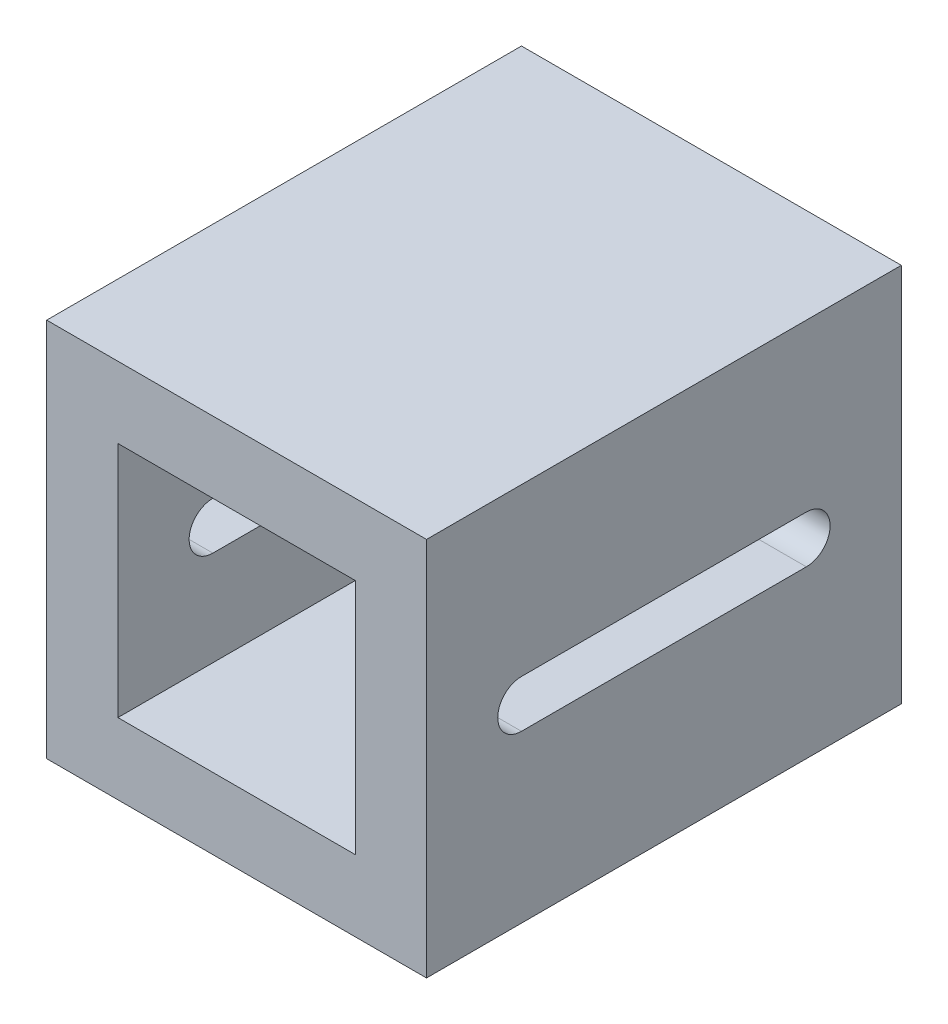
SolidWorks part; units mm, degrees
ref_plane "前视基准面" through (0, 0, 0) normal (0, 0, 1) x (1, 0, 0)
ref_plane "上视基准面" through (0, 0, 0) normal (0, 1, 0) x (1, 0, 0)
ref_plane "右视基准面" through (0, 0, 0) normal (1, 0, 0) x (0, 0, -1)
sketch "草图1" plane through (0, 0, 0) normal (0, 0, 1) x (1, 0, 0)
  line L1 (0, 0) -> (16, 0)
  line L2 (0, 0) -> (0, 16)
  line L3 (0, 16) -> (16, 16)
  line L4 (16, 0) -> (16, 16)
  line L5 (3, 3) -> (13, 3)
  line L6 (3, 3) -> (3, 13)
  line L7 (3, 13) -> (13, 13)
  line L8 (13, 3) -> (13, 13)
extrude "凸台-拉伸1" add sketch "草图1" along normal blind 20
sketch "草图2" plane through (16, 0, 0) normal (1, 0, 0) x (0, 0, -1)
  line L0 (-16, 9) -> (-4, 9)
  line L1 (-4, 9) -> (-4, 7)
  line L2 (-4, 7) -> (-16, 7)
  line L3 (-16, 7) -> (-16, 9)
  circle A0 centre (-16, 8) radius 1
  circle A1 centre (-4, 8) radius 1
  point P0 (-16, 8)
  point P1 (-4, 8)
  point P2 (-16, 8)
extrude "切除-拉伸1" cut sketch "草图2" against normal blind 16 contours A1 L0 A0 L2 | L1 A1 | L1 A1 | L3 A0 | L3 A0
